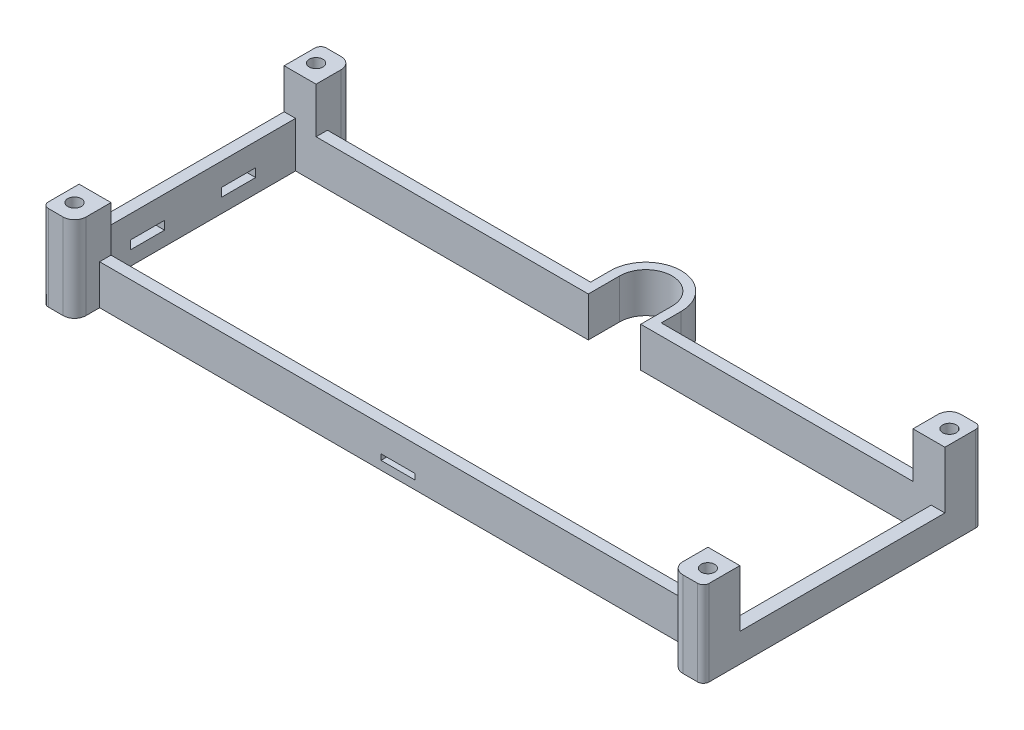
SolidWorks part; units mm, degrees
material "ABS PC"
ref_plane "Front Plane" through (0, 0, 0) normal (0, 0, 1) x (1, 0, 0)
ref_plane "Top Plane" through (0, 0, 0) normal (0, 1, 0) x (1, 0, 0)
ref_plane "Right Plane" through (0, 0, 0) normal (1, 0, 0) x (0, 0, -1)
sketch "Sketch1" plane through (0, 0, 0) normal (0, 1, 0) x (1, 0, 0)
  line L0 (2.4, -23.4) -> (2.4, 23.4)
  line L6 (0, 18) -> (0, -18)
  line L7 (0, -18) -> (-15, -18)
  line L8 (-15, -18) -> (-15, -20)
  line L9 (-15, -20) -> (-3.2, -20)
  line L10 (-3.2, -20) -> (-3.2, -22.4)
  line L11 (-1.2, -24.4) -> (1.4, -24.4)
  line L12 (0, 0) -> (8.7, 0) construction
  line L13 (-1.2, 24.4) -> (1.4, 24.4)
  line L14 (-3.2, 20) -> (-3.2, 22.4)
  line L15 (-15, 20) -> (-3.2, 20)
  line L16 (-15, 18) -> (-15, 20)
  line L17 (0, 18) -> (-15, 18)
  arc A2 (-3.2, -22.4) -> (-1.2, -24.4) centre (-1.2, -22.4) ccw
  arc A3 (1.4, -24.4) -> (2.4, -23.4) centre (1.4, -23.4) ccw
  arc A4 (1.4, 24.4) -> (2.4, 23.4) centre (1.4, 23.4) cw
  arc A5 (-3.2, 22.4) -> (-1.2, 24.4) centre (-1.2, 22.4) cw
  circle A6 centre (0, -21.2) radius 1.2
  circle A7 centre (0, 21.2) radius 1.2
  point P22 (2.4, 0)
  point P29 (0, 0)
  dimension "D7" = 2
  dimension "D8" = 1
  dimension "D14" = 2.4
  dimension "D1" = 24.4
  dimension "D2" = 2.4
  dimension "D3" = 2
  dimension "D4" = 18
  dimension "D5" = 15
  dimension "D6" = 5.6
  dimension "D9" = 1
  dimension "D10" = 2.6
  dimension "D11" = 1
  dimension "D12" = 2
  dimension "D13" = 2
  dimension "D15" = 3.2
  dimension "D16" = 2.4
extrude "Boss-Extrude1" add sketch "Sketch1" along normal blind 15
sketch "Sketch3" plane through (0, 0, 0) normal (0, 1, 0) x (1, 0, 0)
  line L0 (-15, -18) -> (-15, 18)
  line L12 (-1.2, -24.4) -> (1.4, -24.4)
  line L13 (-3.2, -20) -> (-3.2, -22.4)
  line L14 (-15, -20) -> (-3.2, -20)
  line L15 (-15, -18) -> (-15, -20)
  line L16 (0, -18) -> (-15, -18)
  line L17 (0, 18) -> (0, -18)
  line L18 (-15, 18) -> (0, 18)
  line L19 (-15, 20) -> (-15, 18)
  line L20 (-3.2, 20) -> (-15, 20)
  line L21 (-3.2, 22.4) -> (-3.2, 20)
  line L22 (1.4, 24.4) -> (-1.2, 24.4)
  line L23 (2.4, -23.4) -> (2.4, 23.4)
  line L24 (-1.2, -24.4) -> (1.4, -24.4) construction
  line L25 (-3.2, -20) -> (-3.2, -22.4) construction
  line L26 (-15, -20) -> (-3.2, -20) construction
  line L27 (-15, -18) -> (-15, -20) construction
  line L28 (0, -18) -> (-15, -18)
  line L29 (0, 18) -> (0, -18)
  line L30 (-15, 18) -> (0, 18)
  line L31 (-15, 20) -> (-15, 18) construction
  line L32 (-3.2, 20) -> (-15, 20) construction
  line L33 (-3.2, 22.4) -> (-3.2, 20) construction
  line L34 (1.4, 24.4) -> (-1.2, 24.4) construction
  line L35 (2.4, -23.4) -> (2.4, 23.4) construction
  arc A4 (1.4, -24.4) -> (2.4, -23.4) centre (1.4, -23.4) ccw
  arc A5 (-3.2, -22.4) -> (-1.2, -24.4) centre (-1.2, -22.4) ccw
  arc A6 (-1.2, 24.4) -> (-3.2, 22.4) centre (-1.2, 22.4) ccw
  arc A7 (2.4, 23.4) -> (1.4, 24.4) centre (1.4, 23.4) ccw
  arc A8 (1.4, -24.4) -> (2.4, -23.4) centre (1.4, -23.4) ccw construction
  arc A9 (-3.2, -22.4) -> (-1.2, -24.4) centre (-1.2, -22.4) ccw construction
  arc A10 (-1.2, 24.4) -> (-3.2, 22.4) centre (-1.2, 22.4) ccw construction
  arc A11 (2.4, 23.4) -> (1.4, 24.4) centre (1.4, 23.4) ccw construction
  dimension "D1" = 0
extrude "Boss-Extrude3" add sketch "Sketch3" along normal blind 1.5
sketch "Sketch4" plane through (-15, 0, 0) normal (-1, 0, 0) x (0, 0, 1)
  line L0 (-18, 1.5) -> (-18, 0)
  line L8 (-20, 0) -> (20, 0)
  line L9 (20, 0) -> (20, 15)
  line L10 (20, 15) -> (18, 15)
  line L11 (18, 15) -> (18, 1.5)
  line L12 (18, 1.5) -> (-18, 1.5)
  line L13 (-18, 1.5) -> (-18, 15)
  line L14 (-18, 15) -> (-20, 15)
  line L15 (-20, 15) -> (-20, 0)
  line L16 (-20, 0) -> (-18, 0)
  line L21 (-18, 1.5) -> (-18, 15)
  line L22 (-18, 15) -> (-20, 15)
  line L23 (-20, 15) -> (-20, 0)
  dimension "D1" = 0
extrude "Boss-Extrude4" add sketch "Sketch4" along normal blind 36
sketch "Sketch6" plane through (0, 15, 0) normal (0, 1, 0) x (1, 0, 0)
  line L0 (-49.4072, 20) -> (-29.2339, 20) construction
  line L1 (-61.8, 20) -> (-61.8, 23.5)
  line L2 (-3.2, 20) -> (-51, 20) construction
  line L3 (-60.2, 20) -> (-60.2, 23.5)
  line L4 (-60.2, 23.5) -> (-51, 23.5) construction
  line L5 (-51, 23.5) -> (-51, 20)
  line L6 (-49.4, 23.5) -> (-49.4, 20)
  line L7 (-60.2, 18) -> (-113.6, 18)
  line L8 (-113.6, 18) -> (-113.6, 23.4)
  line L9 (-112.6, 24.4) -> (-110, 24.4)
  line L10 (-108, 22.4) -> (-108, 20)
  line L11 (-108, 20) -> (-61.8, 20)
  line L12 (-60.2, 20) -> (-60.2, 18)
  line L13 (-51, 20) -> (-49.4, 20)
  line L14 (0, 0) -> (-50000, 0) construction
  line L15 (-113.6, -18) -> (-15, -18)
  line L16 (-108, -20) -> (-15, -20)
  line L17 (-108, -22.4) -> (-108, -20)
  line L18 (-112.6, -24.4) -> (-110, -24.4)
  line L19 (-113.6, -18) -> (-113.6, -23.4)
  line L20 (0, -18) -> (-15, -18) construction
  line L21 (-15, -18) -> (-15, -20) construction
  line L22 (-15, -18) -> (-15, -20)
  line L23 (0, -21.2) -> (-111.2, -21.2) construction
  arc A0 (-60.2, 23.5) -> (-51, 23.5) centre (-55.6, 23.5) cw
  arc A1 (-113.6, 23.4) -> (-112.6, 24.4) centre (-112.6, 23.4) cw
  arc A2 (-110, 24.4) -> (-108, 22.4) centre (-110, 22.4) cw
  arc A3 (-61.8, 23.5) -> (-49.4, 23.5) centre (-55.6, 23.5) cw
  circle A4 centre (-111.2, 21.2) radius 1.2
  circle A5 centre (-111.2, -21.2) radius 1.2
  arc A6 (-110, -24.4) -> (-108, -22.4) centre (-110, -22.4) ccw
  arc A7 (-113.6, -23.4) -> (-112.6, -24.4) centre (-112.6, -23.4) ccw
  point P41 (-55.6, -21.2)
  dimension "D5" = 1
  dimension "D6" = 2
  dimension "D7" = 2.4
  dimension "D15" = 2
  dimension "D17" = 1
  dimension "D14" = 2.4
  dimension "D11" = 4.6
  dimension "D1" = 9.2
  dimension "D2" = 3.5
  dimension "D4" = 2
  dimension "D8" = 2.4
  dimension "D9" = 3.2
  dimension "D10" = 2.6
  dimension "D12" = 2.4
  dimension "D13" = 3.2
  dimension "D16" = 2.6
  dimension "D18" = 5.4
  dimension "D19" = 2.4
  dimension "D20" = 3.2
  dimension "D21" = 111.2
  dimension "D3" = 1.6
extrude "Boss-Extrude5" add sketch "Sketch6" against normal blind 15
sketch "Sketch7" plane through (0, 0, 0) normal (0, -1, 0) x (1, 0, 0)
  line L0 (-113.6, -18) -> (-60.2, -18) construction
  line L1 (-113.6, 18) -> (-111.6, 18)
  line L2 (-113.6, 18) -> (-113.6, -18)
  line L3 (-113.6, -18) -> (-111.6, -18)
  line L4 (-111.6, 18) -> (-111.6, -18)
  dimension "D1" = 2
extrude "Boss-Extrude6" add sketch "Sketch7" against normal blind 8
sketch "Sketch8" plane through (0, 0, 18) normal (0, 0, -1) x (-1, 0, 0)
  line L0 (108, 0) -> (3.2, 0) construction
  line L1 (58.6, 1.5) -> (52.6, 1.5)
  line L2 (58.6, 1.5) -> (58.6, 2.5)
  line L3 (58.6, 2.5) -> (52.6, 2.5)
  line L4 (52.6, 1.5) -> (52.6, 2.5)
  line L5 (108, 0) -> (3.2, 0) construction
  line L6 (55.6, 0) -> (55.6, 50000) construction
  point P8 (55.6, 0)
  point P9 (55.6, 1.5)
  dimension "D1" = 6
  dimension "D2" = 1
  dimension "D3" = 1.5
extrude "Cut-Extrude1" cut sketch "Sketch8" against normal blind 5
sketch "Sketch9" plane through (-111.6, 0, 0) normal (1, 0, 0) x (0, 0, -1)
  line L0 (0, 0) -> (0, 50000) construction
  line L1 (11, 2.5) -> (5, 2.5)
  line L2 (11, 2.5) -> (11, 4)
  line L3 (11, 4) -> (5, 4)
  line L4 (5, 2.5) -> (5, 4)
  line L9 (18, 0) -> (-18, 0) construction
  line L10 (18, 8) -> (-18, 8) construction
  line L11 (-5, 2.5) -> (-5, 4)
  line L12 (-11, 4) -> (-5, 4)
  line L13 (-11, 2.5) -> (-11, 4)
  line L14 (-11, 2.5) -> (-5, 2.5)
  point P8 (0, 0)
  point P11 (0, 8)
  dimension "D1" = 5
  dimension "D2" = 6
  dimension "D3" = 1.5
  dimension "D4" = 2.5
extrude "Cut-Extrude2" cut sketch "Sketch9" against normal blind 5
sketch "Sketch10" plane through (0, 0, -20) normal (0, 0, -1) x (-1, 0, 0)
  line L0 (108, 0) -> (108, 15) construction
  line L1 (108, 7) -> (3.2, 7)
  line L2 (108, 7) -> (108, 15)
  line L3 (108, 15) -> (3.2, 15)
  line L4 (3.2, 7) -> (3.2, 15)
  dimension "D1" = 8
extrude "Cut-Extrude3" cut sketch "Sketch10" against normal through all and the other way through all
sketch "Sketch11" plane through (2.4, 0, 0) normal (1, 0, 0) x (0, 0, -1)
  line L0 (18, 0) -> (-18, 0) construction
  line L1 (18, 0) -> (-18, 0) construction
  line L2 (18, 5) -> (18, 15)
  line L3 (-23.4, 15) -> (23.4, 15) construction
  line L4 (18, 15) -> (-18, 15)
  line L5 (-18, 15) -> (-18, 5)
  line L6 (-18, 5) -> (18, 5)
  dimension "D1" = 10
extrude "Cut-Extrude4" cut sketch "Sketch11" against normal blind 10
sketch "Sketch12" plane through (0, 0, 0) normal (0, -1, 0) x (1, 0, 0)
  line L0 (0, 18) -> (0, -18) construction
  line L1 (0, 18) -> (0, -18)
  line L2 (0, -18) -> (-15, -18)
  line L3 (-15, -18) -> (-15, 18)
  line L4 (-15, 18) -> (0, 18)
extrude "Cut-Extrude5" cut sketch "Sketch12" against normal blind 10
ref_plane "Plane1" through (0, 0, 18) normal (-1, 0, 0) x (0, 0, 1)
equation "\"ˇ5\"=10.0979"
